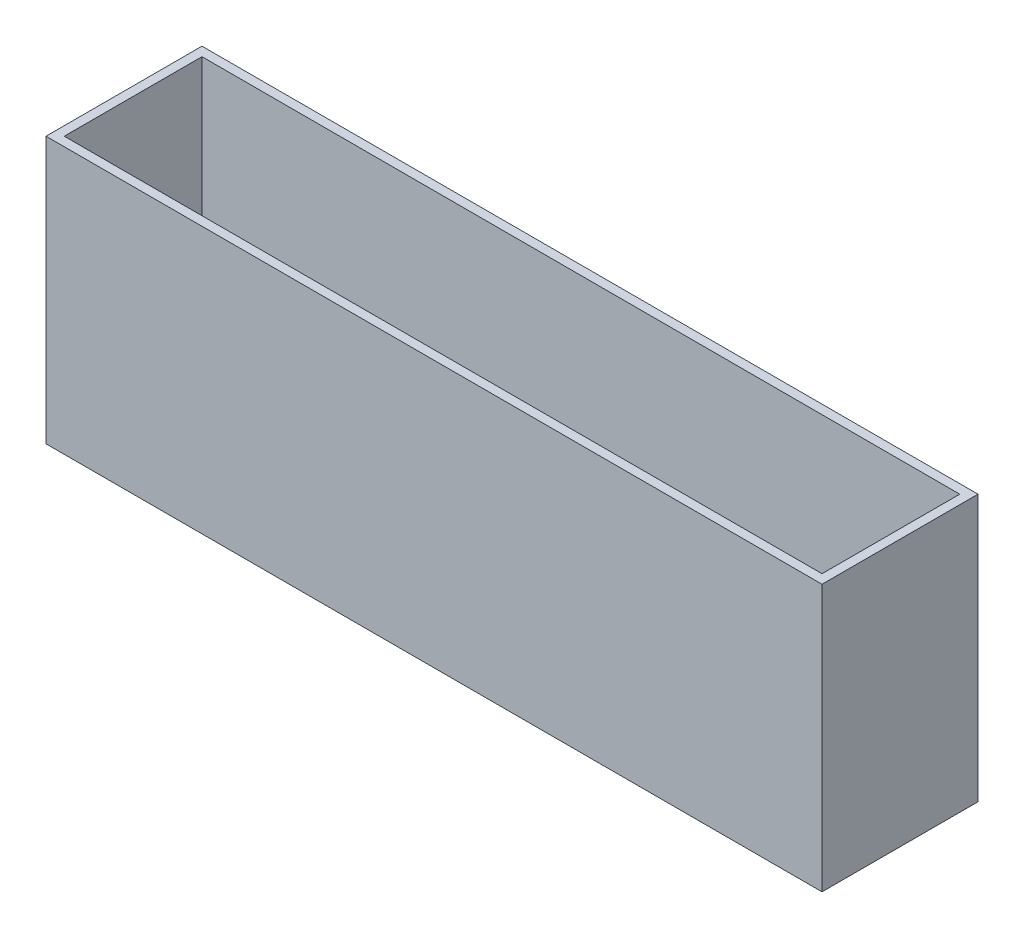
SolidWorks part; units mm, degrees
ref_plane "Front Plane" through (0, 0, 0) normal (0, 0, 1) x (1, 0, 0)
ref_plane "Top Plane" through (0, 0, 0) normal (0, 1, 0) x (1, 0, 0)
ref_plane "Right Plane" through (0, 0, 0) normal (1, 0, 0) x (0, 0, -1)
sketch "Sketch1" plane through (0, 0, 0) normal (0, 0, 1) x (1, 0, 0)
  line L0 (45.4216, 53.4962) -> (-228.8418, 53.4962) construction
  line L7 (46.4216, 52.5339) -> (46.4216, -445.9962) construction
  line L8 (-218.8418, 35.7162) -> (36.4216, 35.7162)
  line L9 (-218.8418, 35.7162) -> (-218.8418, -51.9138)
  line L10 (-218.8418, -51.9138) -> (36.4216, -51.9138)
  line L11 (36.4216, 35.7162) -> (36.4216, -51.9138)
  line L12 (-228.8418, 53.4962) -> (-228.8418, -444.851) construction
  dimension "D1" = 10
  dimension "D2" = 10
  dimension "D3" = 87.63
  dimension "D4" = 17.78
extrude "Boss-Extrude1" add sketch "Sketch1" along normal blind 51.308
shell "Shell1" thickness 3
